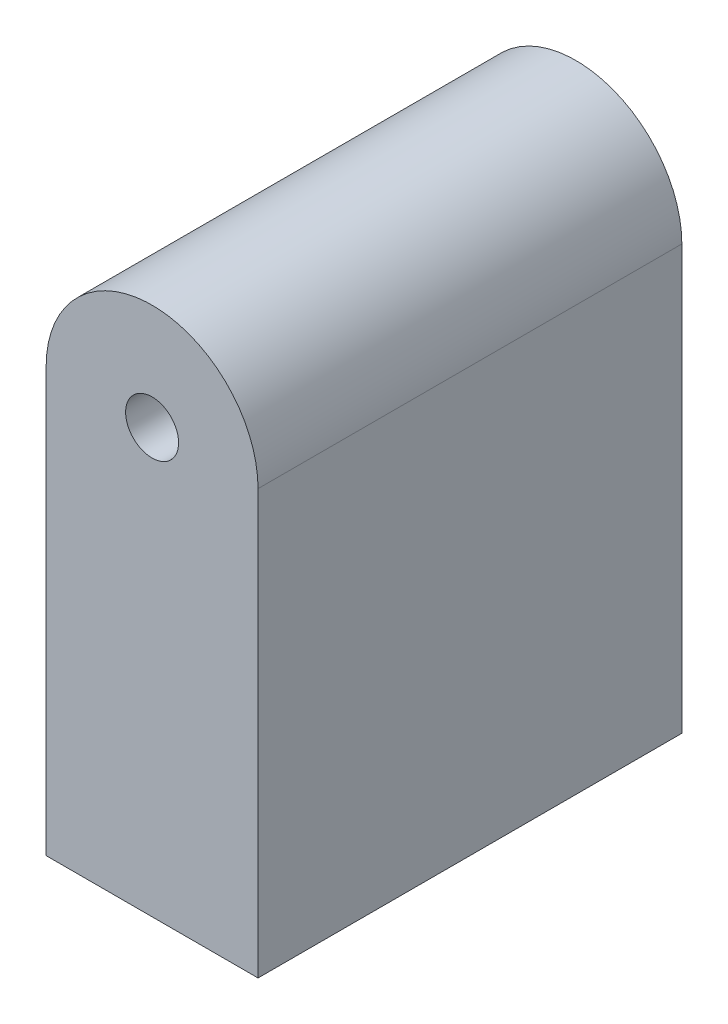
SolidWorks part; units mm, degrees
ref_plane "Front Plane" through (0, 0, 0) normal (0, 0, 1) x (1, 0, 0)
ref_plane "Top Plane" through (0, 0, 0) normal (0, 1, 0) x (1, 0, 0)
ref_plane "Right Plane" through (0, 0, 0) normal (1, 0, 0) x (0, 0, -1)
sketch "Sketch1" plane through (0, 0, 0) normal (0, 0, 1) x (1, 0, 0)
  line L1 (0, 0) -> (25.4, 0)
  line L2 (0, 0) -> (0, 50.8)
  line L3 (0, 50.8) -> (25.4, 50.8)
  line L4 (25.4, 0) -> (25.4, 50.8)
  line L5 (0, 0) -> (25.4, 50.8) construction
  line L6 (0, 50.8) -> (25.4, 0) construction
  circle A0 centre (12.7, 50.8) radius 12.7
  circle A1 centre (12.7, 50.8) radius 3.175
  point P4 (12.7, 25.4)
  dimension "D3" = 6.35
  dimension "D1" = 25.4
  dimension "D2" = 50.8
extrude "Boss-Extrude1" add sketch "Sketch1" along normal blind 50.8 contours A1 L3 A0 | A1 L3 A0 | A0 L2 L1 L4
